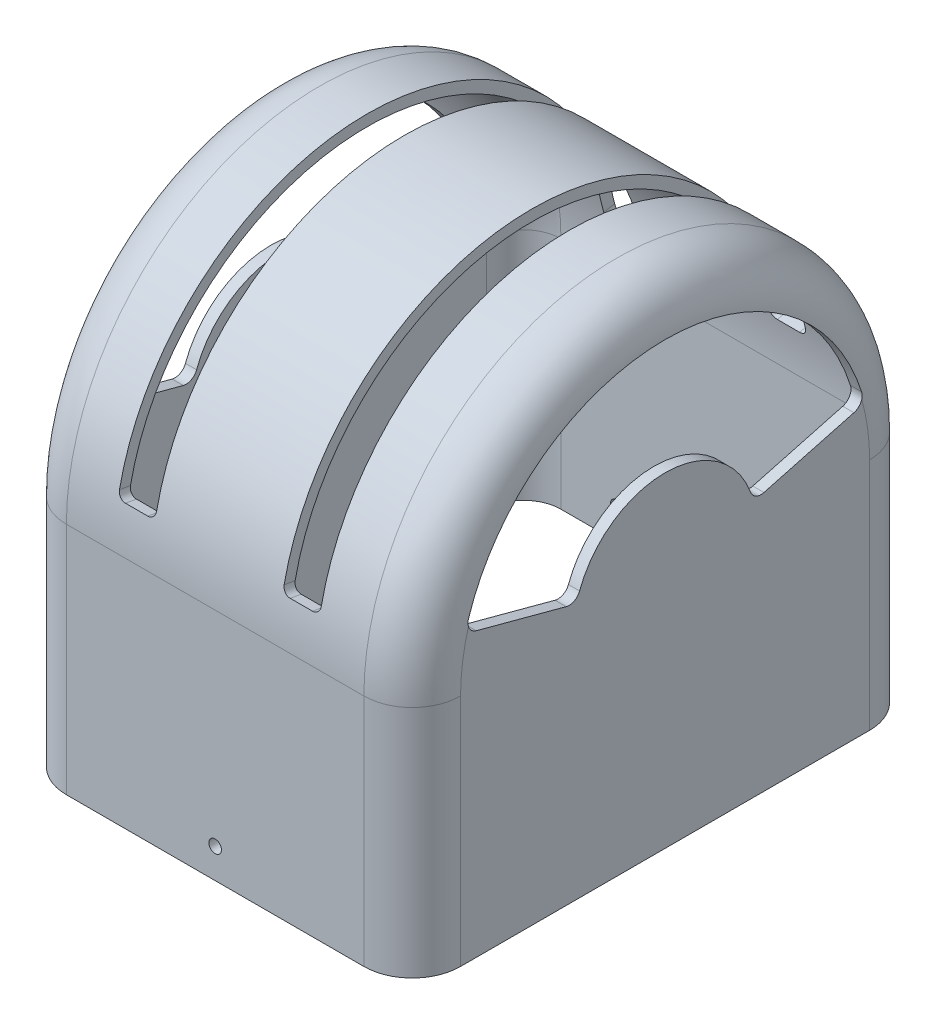
SolidWorks part; units mm, degrees
ref_plane "Front" through (0, 0, 0) normal (0, 0, 1) x (1, 0, 0)
ref_plane "Top" through (0, 0, 0) normal (0, 1, 0) x (1, 0, 0)
ref_plane "Right" through (0, 0, 0) normal (1, 0, 0) x (0, 0, -1)
sketch "Sketch1" plane through (0, -21.2328, 56.11) normal (-1, 0, 0) x (0, -1, 0)
  line L0 (-15.2328, 8.89) -> (-81.2328, 8.89) construction
  line L1 (-15.2328, -121.11) -> (-15.2328, 8.89) construction
  line L2 (-81.2328, -121.11) -> (-15.2328, -121.11) construction
  line L3 (-15.2328, 8.89) -> (-81.2328, 8.89) construction
  line L4 (-15.2328, -121.11) -> (-15.2328, 8.89) construction
  line L5 (-81.2328, -121.11) -> (-15.2328, -121.11) construction
  line L6 (-15.2328, 11.89) -> (-81.2328, 11.89)
  line L7 (-81.2328, -124.11) -> (-15.2328, -124.11)
  line L8 (-15.2328, 11.89) -> (-15.2328, -124.11)
  line L9 (-18.2328, -124.11) -> (-18.2328, 11.89)
  line L12 (-18.2328, -111.11) -> (-18.2328, -1.11) construction
  arc A0 (-81.2328, 8.89) -> (-81.2328, -121.11) centre (-81.2328, -56.11) ccw construction
  arc A1 (-81.2328, 8.89) -> (-81.2328, -121.11) centre (-81.2328, -56.11) ccw construction
  arc A2 (-81.2328, 11.89) -> (-81.2328, -124.11) centre (-81.2328, -56.11) ccw
  dimension "D1" = 3
extrude "Boss-Extrude1" add sketch "Sketch1" against normal up to surface (53 mm away) and the other way up to surface (53 mm away) contours A2 L6 L9 L7
fillet "Fillet1" radius 13 6 edges at (53, 28.5, -68) (53, 28.5, 68) (-53, 28.5, -68) (-53, 28.5, 68) (53, 128, 0) (-53, 128, 0)
shell "Shell1" thickness 3
sketch "Sketch2" plane through (0, 0, 0) normal (1, 0, 0) x (0, 0, -1)
  line L0 (24.1481, 66.4705) -> (53.1259, 74.235) construction
  line L1 (-24.1481, 66.4705) -> (-53.1259, 74.235) construction
  line L2 (-26.5824, 66.6051) -> (-50.783, 73.0896)
  line L3 (26.5824, 66.6051) -> (50.783, 73.0896)
  line L4 (-23.7897, 65.8568) -> (-53.7361, 73.8809) construction
  line L5 (23.7897, 65.8568) -> (53.7361, 73.8809) construction
  arc A0 (53.1259, 74.235) -> (-53.1259, 74.235) centre (0, 60) ccw construction
  arc A1 (24.1481, 66.4705) -> (-24.1481, 66.4705) centre (0, 60) ccw construction
  arc A2 (53.1259, 74.235) -> (-53.1259, 74.235) centre (0, 60) ccw construction
  arc A3 (24.1481, 66.4705) -> (-24.1481, 66.4705) centre (0, 60) ccw construction
  arc A4 (52.864, 76.901) -> (-52.864, 76.901) centre (0, 60) ccw
  arc A5 (22.9907, 68.4662) -> (-22.9907, 68.4662) centre (0, 60) ccw
  arc A6 (53.7361, 73.8809) -> (-53.7361, 73.8809) centre (0, 60) ccw construction
  arc A7 (-50.783, 73.0896) -> (-52.864, 76.901) centre (-50.0065, 75.9874) cw
  arc A8 (23.7897, 65.8568) -> (-23.7897, 65.8568) centre (0, 60) ccw construction
  arc A9 (-26.5824, 66.6051) -> (-22.9907, 68.4662) centre (-25.8059, 69.5029) ccw
  arc A10 (22.9907, 68.4662) -> (26.5824, 66.6051) centre (25.8059, 69.5029) ccw
  arc A11 (50.783, 73.0896) -> (52.864, 76.901) centre (50.0065, 75.9874) ccw
  dimension "D2" = 3
  dimension "D1" = 0.5
extrude "Cut-Extrude1" cut sketch "Sketch2" against normal through all both and the other way through all
sketch "Sketch3" plane through (0, 0, 0) normal (1, 0, 0) x (0, 0, -1)
  line L0 (53.1259, 74.235) -> (0, 60) construction
  line L1 (0, 60) -> (-53.1259, 74.235) construction
  line L2 (53.1259, 74.235) -> (0, 60) construction
  line L3 (0, 60) -> (-53.1259, 74.235) construction
  line L4 (0, 60) -> (98.4808, 77.3648)
  line L5 (0, 60) -> (-98.4808, 77.3648)
  line L6 (0, 60) -> (-53.1259, 74.235) construction
  arc A0 (53.1259, 74.235) -> (-53.1259, 74.235) centre (0, 60) ccw construction
  arc A1 (53.1259, 74.235) -> (-53.1259, 74.235) centre (0, 60) ccw construction
  arc A2 (98.4808, 77.3648) -> (-98.4808, 77.3648) centre (0, 60) ccw
  dimension "D1" = 100
  dimension "D2" = 5
  dimension "D3" = 5
ref_plane "Plane1" through (-22.145, 0, 0) normal (-1, 0, 0) x (0, 0, 1)
ref_plane "Plane2" through (22.145, 0, 0) normal (1, 0, 0) x (0, 0, -1)
extrude "Cut-Extrude2" cut sketch "Sketch3" against normal mid plane 10 from surface at -22.145 starting at plane "Plane1"
mirror "Mirror1" about plane through (0, 0, 0) normal (1, 0, 0) of "Cut-Extrude2"
fillet "Fillet2" radius 2 8 edges at (27.145, 71.5476, -65.4897) (17.145, 71.5476, -65.4897) (-17.145, 71.5476, -65.4897) (-27.145, 71.5476, -65.4897) (-27.145, 71.5476, 65.4897) (-17.145, 71.5476, 65.4897) (17.145, 71.5476, 65.4897) (27.145, 71.5476, 65.4897)
sketch "Sketch4" plane through (0, 0, 68) normal (0, 0, 1) x (1, 0, 0)
  line L4 (-40, -3) -> (40, -3)
  line L5 (40, -3) -> (40, 60)
  line L6 (40, 60) -> (-40, 60)
  line L7 (-40, 60) -> (-40, -3)
  line L8 (-40, -3) -> (40, -3) construction
  line L9 (40, -3) -> (40, 60) construction
  line L10 (40, 60) -> (-40, 60) construction
  line L11 (-40, 60) -> (-40, -3) construction
  circle A0 centre (0, 5) radius 1.7 construction
  circle A1 centre (0, 5) radius 1.7
  dimension "D1" = 0
extrude "Cut-Extrude3" cut sketch "Sketch4" against normal blind 10
sketch "Sketch5" plane through (0, 0, -68) normal (0, 0, -1) x (-1, 0, 0)
  line L4 (40, 60) -> (-40, 60)
  line L5 (-40, 60) -> (-40, -3)
  line L6 (-40, -3) -> (40, -3)
  line L7 (40, -3) -> (40, 60)
  line L8 (40, 60) -> (-40, 60) construction
  line L9 (-40, 60) -> (-40, -3) construction
  line L10 (-40, -3) -> (40, -3) construction
  line L11 (40, -3) -> (40, 60) construction
  circle A0 centre (-25, 5) radius 1.7 construction
  circle A1 centre (25, 5) radius 1.7 construction
  circle A2 centre (-25, 5) radius 1.7
  circle A3 centre (25, 5) radius 1.7
  dimension "D1" = 0
extrude "Cut-Extrude6" cut sketch "Sketch5" against normal blind 10 contours A3 | A2
equation "\"D3@Sketch3\"=\"D2@Sketch3\""
